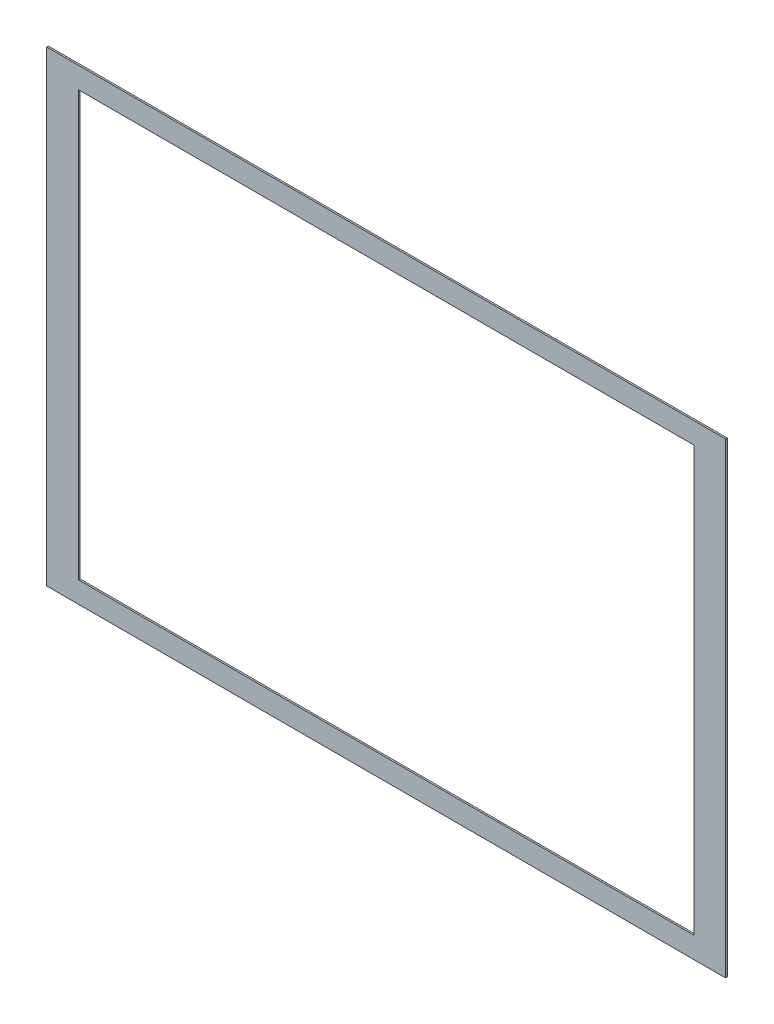
SolidWorks part; units mm, degrees
ref_plane "Front Plane" through (0, 0, 0) normal (0, 0, 1) x (1, 0, 0)
ref_plane "Top Plane" through (0, 0, 0) normal (0, 1, 0) x (1, 0, 0)
ref_plane "Right Plane" through (0, 0, 0) normal (1, 0, 0) x (0, 0, -1)
other "Configuration Table"
sketch "Sketch1" plane through (0, 0, 0) normal (0, 0, 1) x (1, 0, 0)
  line L1 (30, 600) -> (670, 600)
  line L2 (30, 600) -> (30, 1040)
  line L3 (30, 1040) -> (670, 1040)
  line L4 (670, 600) -> (670, 1040)
extrude "PACK_panel_kutulama_1" add sketch "Sketch1" along normal blind 1.5 from offset 38.5 separate body
sketch "Sketch2" plane through (0, 0, 0) normal (0, 0, 1) x (1, 0, 0)
  line L1 (60, 620) -> (640, 620)
  line L2 (60, 620) -> (60, 1020)
  line L3 (60, 1020) -> (640, 1020)
  line L4 (640, 620) -> (640, 1020)
extrude "PACK_panel_kutulama_2" cut sketch "Sketch2" along normal blind 3.5 from offset 37.5
